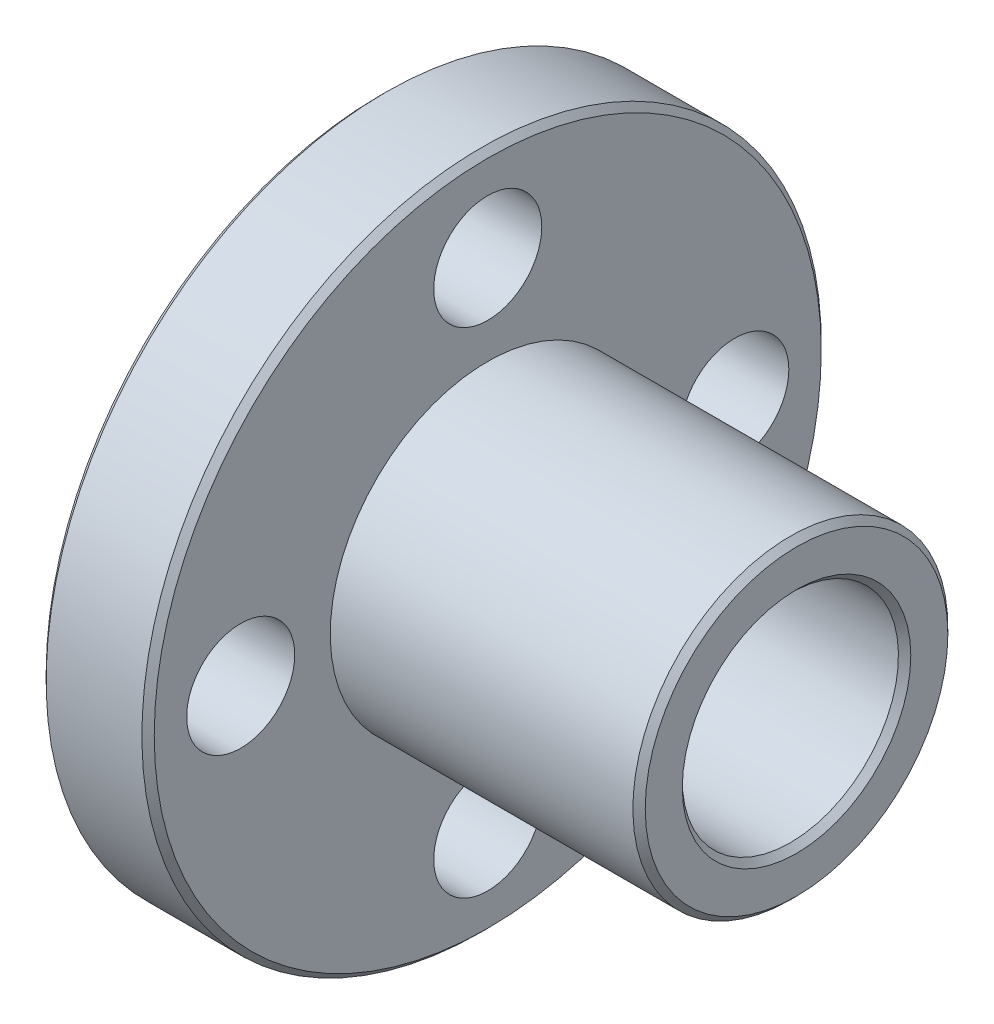
SolidWorks part; units mm, degrees
material "Brass"
ref_plane "Front Plane" through (0, 0, 0) normal (0, 0, 1) x (1, 0, 0)
ref_plane "Top Plane" through (0, 0, 0) normal (0, 1, 0) x (1, 0, 0)
ref_plane "Right Plane" through (0, 0, 0) normal (1, 0, 0) x (0, 0, -1)
sketch "Sketch1" plane through (0, 0, 0) normal (0, 0, 1) x (1, 0, 0)
  line L0 (0, 0) -> (13.5, 0) construction
  line L1 (0, 5.1) -> (0, 11)
  line L2 (0, 11) -> (3.5, 11)
  line L3 (3.5, 11) -> (3.5, 5.1)
  line L4 (3.5, 5.1) -> (13.5, 5.1)
  line L5 (13.5, 5.1) -> (13.5, 3.5)
  line L6 (13.5, 3.5) -> (-1.5, 3.5)
  line L7 (0, 5.1) -> (-1.5, 5.1)
  line L8 (-1.5, 5.1) -> (-1.5, 3.5)
  point P11 (0, 0)
  dimension "D1" = 7
  dimension "D2" = 10.2
  dimension "D3" = 22
  dimension "D4" = 3.5
  dimension "D5" = 15
  dimension "D6" = 1.5
revolve "Revolve1" add sketch "Sketch1" angle 360 about L0
chamfer "Chamfer1" distance 0.2 angle 45 6 edges at (13.5, -3.5, 0) (13.5, -5.1, 0) (3.5, -11, 0) (0, -11, 0) (-1.5, -3.5, 0) (-1.5, -5.1, 0)
sketch "Sketch3" plane through (3.5, 0, 0) normal (1, 0, 0) x (0, 0, -1)
  circle A0 centre (0, 0) radius 8 construction
  point P3 (0, 8)
  dimension "D1" = 16
hole_wizard "M3 Clearance Hole1" positions "Sketch4" profile "Sketch5" hole size "M3" standard "ISO"
sketch "Sketch4" plane through (3.5, 0, 0) normal (1, 0, 0) x (0, 0, -1)
  point P0 (0, 8)
sketch "Sketch5" plane through (3.5, 8, 0) normal (0, 1, 0) x (0, 0, -1)
  line L0 (0, 0) -> (0, 4.0515)
  line L1 (0, 4.0515) -> (1.75, 3)
  line L2 (1.75, 3) -> (1.75, 0)
  line L5 (1.75, 0) -> (0, 0)
  line L10 (0, 4.0515) -> (-1.75, 3) construction
  line L11 (0, -6.35) -> (0, 107.95) construction
  dimension "Hole Dia." = 3.5
  dimension "Hole Depth" = 3
  dimension "Drill Angle" = 118
pattern_circular "CirPattern1" count 4 over 360 about axis through (0, 0, 0) along (1, 0, 0) of "M3 Clearance Hole1"
